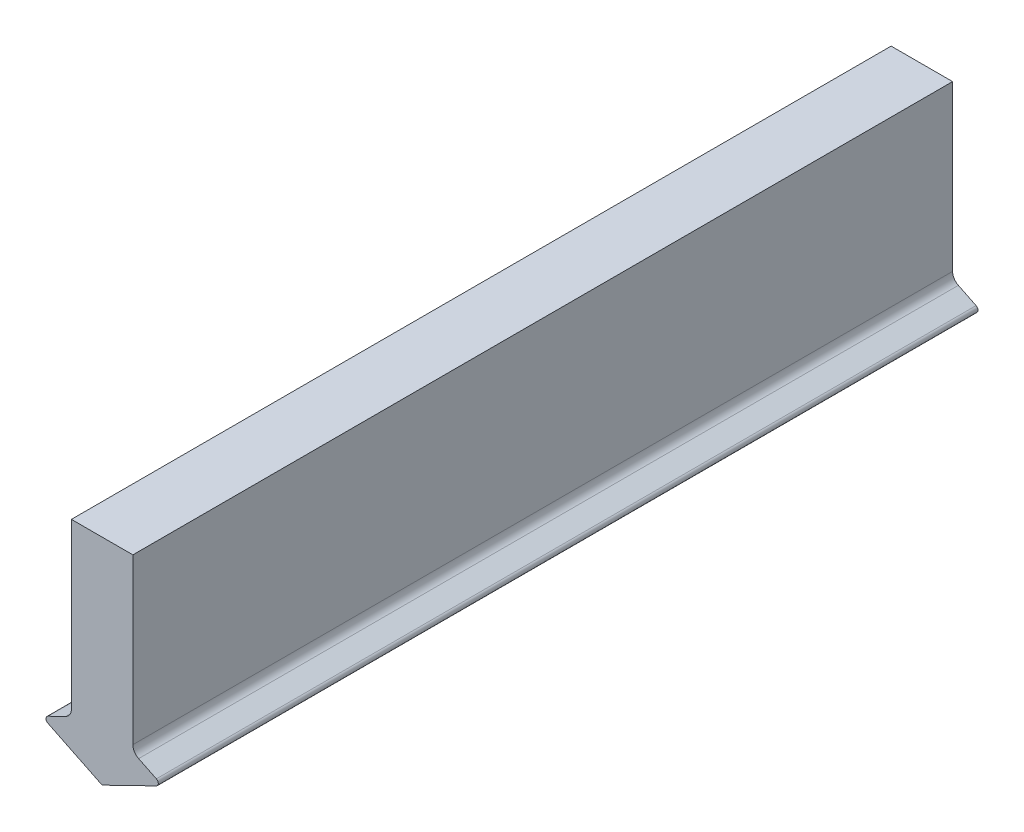
SolidWorks part; units mm, degrees
material "ABS generico"
ref_plane "Piano frontale" through (0, 0, 0) normal (0, 0, 1) x (1, 0, 0)
ref_plane "Piano superiore" through (0, 0, 0) normal (0, 1, 0) x (1, 0, 0)
ref_plane "Piano destro" through (0, 0, 0) normal (1, 0, 0) x (0, 0, -1)
sketch "Schizzo1" plane through (0, 0, 0) normal (0, 0, 1) x (1, 0, 0)
  line L0 (0, 0) -> (-3.1752, 1.5487)
  line L1 (-3.1752, 1.9082) -> (-2.137, 2.4145)
  line L2 (-1.8, 2.9538) -> (-1.8, 12.5789)
  line L3 (-1.8, 12.5789) -> (1.8, 12.5789)
  line L4 (1.8, 12.5789) -> (1.8, 2.9538)
  line L5 (2.137, 2.4145) -> (3.1752, 1.9082)
  line L6 (3.1752, 1.5487) -> (0, 0)
  line L7 (0, 0) -> (0, 12.5789) construction
  arc A0 (3.1752, 1.5487) -> (3.1752, 1.9082) centre (3.0875, 1.7284) ccw
  arc A1 (-3.1752, 1.9082) -> (-3.1752, 1.5487) centre (-3.0875, 1.7284) ccw
  arc A2 (2.137, 2.4145) -> (1.8, 2.9538) centre (2.4, 2.9538) cw
  arc A3 (-2.137, 2.4145) -> (-1.8, 2.9538) centre (-2.4, 2.9538) ccw
  point P9 (-13.5974, 8.4417)
  point P10 (-1.4805, 2.5871)
  point P15 (-3.5438, 1.7284)
  point P20 (-1.8, 2.5789)
  dimension "D6" = 0.2
  dimension "D7" = 0.6
  dimension "D1" = 128
  dimension "D2" = 3.9428
  dimension "D3" = 52
  dimension "D4" = 1.9401
  dimension "D5" = 10
extrude "Estrusione-Estrusione1" add sketch "Schizzo1" along normal blind 48
